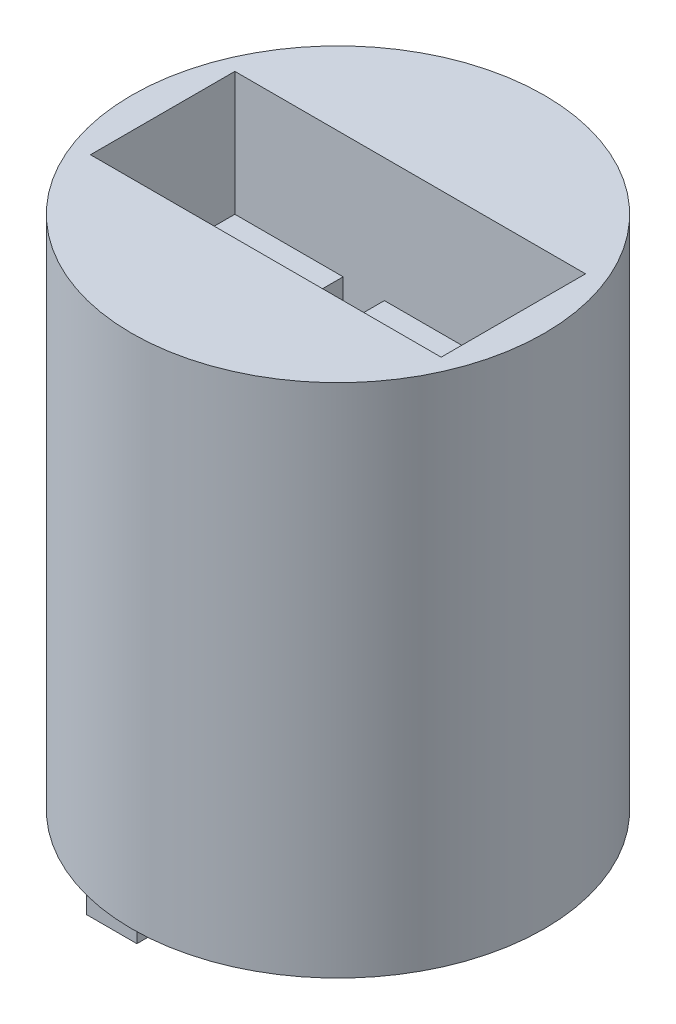
SolidWorks part; units mm, degrees
ref_plane "Front Plane" through (0, 0, 0) normal (0, 0, 1) x (1, 0, 0)
ref_plane "Top Plane" through (0, 0, 0) normal (0, 1, 0) x (1, 0, 0)
ref_plane "Right Plane" through (0, 0, 0) normal (1, 0, 0) x (0, 0, -1)
sketch "Sketch1" plane through (0, 0, 0) normal (0, 1, 0) x (1, 0, 0)
  circle A0 centre (0, 0) radius 10
  dimension "D1" = 20
extrude "Boss-Extrude1" add sketch "Sketch1" along normal blind 25
sketch "Sketch2" plane through (0, 0, 0) normal (0, -1, 0) x (-1, 0, 0)
  line L1 (8.5, 2.5) -> (7.25, 2.5)
  line L2 (8.5, 2.5) -> (8.5, -2.5)
  line L3 (8.5, -2.5) -> (7.25, -2.5)
  line L4 (7.25, 2.5) -> (7.25, -2.5)
  point P4 (7.25, 0)
  dimension "D1" = 5
  dimension "D2" = 1.25
  dimension "D3" = 7.25
extrude "Boss-Extrude2" add sketch "Sketch2" along normal blind 8 separate body
sketch "Sketch3" plane through (-8.5, 0, 0) normal (-1, 0, 0) x (0, 0, 1)
  line L0 (-2.5, -8) -> (-2.5, 0)
  line L1 (-2.5, 0) -> (2.5, 0)
  line L2 (2.5, 0) -> (2.5, -8)
  line L3 (2.5, -8) -> (1.5, -8)
  line L4 (2.5, -8) -> (-2.5, -8) construction
  line L5 (1.5, -8) -> (1.5, -0.75)
  line L6 (1.5, -0.75) -> (-1.5, -0.75)
  line L7 (-1.5, -0.75) -> (-1.5, -8)
  line L8 (-1.5, -8) -> (-2.5, -8)
  dimension "D1" = 1
  dimension "D2" = 1
  dimension "D3" = 0.75
extrude "Boss-Extrude3" add sketch "Sketch3" along normal blind 1.2
sketch "Sketch4" plane through (0, 25, 0) normal (0, 1, 0) x (1, 0, 0)
  line L0 (-10, 0) -> (10, 0) construction
  line L1 (-8.5, -3.5) -> (8.5, -3.5)
  line L2 (-8.5, -3.5) -> (-8.5, 3.5)
  line L3 (-8.5, 3.5) -> (8.5, 3.5)
  line L4 (8.5, -3.5) -> (8.5, 3.5)
  circle A0 centre (0, 0) radius 10 construction
  point P9 (-8.5, 0)
  dimension "D1" = 7
  dimension "D2" = 17
  dimension "D3" = 1.5
extrude "Cut-Extrude1" cut sketch "Sketch4" against normal blind 6
sketch "Sketch5" plane through (0, 19, 0) normal (0, 1, 0) x (1, 0, 0)
  line L0 (8.5, 0) -> (-1.25, 0) construction
  line L1 (8.5, -3.5) -> (8.5, 3.5) construction
  line L2 (8.5, 3.5) -> (-8.5, 3.5) construction
  line L3 (-1.25, 3.5) -> (-3.25, 3.5)
  line L4 (-1.25, 3.5) -> (-1.25, -3.5)
  line L5 (-1.25, -3.5) -> (-3.25, -3.5)
  line L6 (-3.25, 3.5) -> (-3.25, -3.5)
  line L7 (-8.5, -3.5) -> (8.5, -3.5) construction
  dimension "D1" = 9.75
  dimension "D2" = 2
extrude "Cut-Extrude2" cut sketch "Sketch5" against normal blind 4
